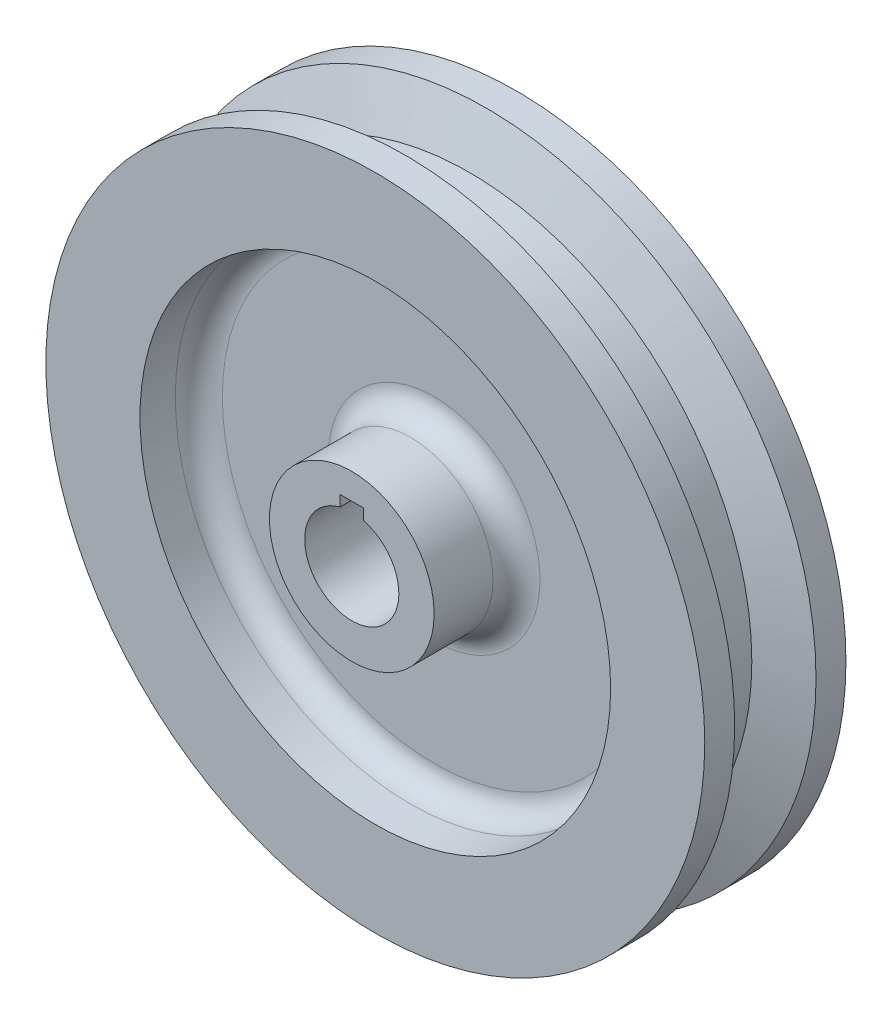
SolidWorks part; units mm, degrees
material "Cast Carbon Steel"
ref_plane "Front Plane" through (0, 0, 0) normal (0, 0, 1) x (1, 0, 0)
ref_plane "Top Plane" through (0, 0, 0) normal (0, 1, 0) x (1, 0, 0)
ref_plane "Right Plane" through (0, 0, 0) normal (1, 0, 0) x (0, 0, -1)
sketch "Sketch1" plane through (0, 0, 0) normal (1, 0, 0) x (0, 0, -1)
  line L0 (-48.3797, 0) -> (2370.6054, 0) construction
  line L1 (-1, 0.5) -> (1, 0.5)
  line L2 (1, 0.5) -> (1, 0.875)
  line L3 (1, 0.875) -> (0.125, 0.875)
  line L4 (0.125, 0.875) -> (0.125, 2.5)
  line L5 (0.125, 2.5) -> (0.75, 2.5)
  line L6 (0.75, 2.5) -> (0.75, 3.5)
  line L7 (0.75, 3.5) -> (0.432, 3.5)
  line L8 (0.432, 3.5) -> (0.25, 3)
  line L9 (0.25, 3) -> (-0.25, 3)
  line L10 (-0.25, 3) -> (-0.432, 3.5)
  line L11 (-0.432, 3.5) -> (-0.75, 3.5)
  line L12 (-0.75, 3.5) -> (-0.75, 2.5)
  line L13 (-0.75, 2.5) -> (-0.125, 2.5)
  line L14 (-0.125, 2.5) -> (-0.125, 0.875)
  line L15 (-0.125, 0.875) -> (-1, 0.875)
  line L16 (-1, 0.875) -> (-1, 0.5)
  point P5 (0, 3)
  point P20 (0, 0.5)
  point P21 (1, 0.6875)
  point P22 (0.591, 3.5)
  dimension "D1" = 0.25
  dimension "D2" = 1
  dimension "D3" = 1.75
  dimension "D4" = 5
  dimension "D5" = 7
  dimension "D6" = 0.5
  dimension "D7" = 2
  dimension "D8" = 1.5
  dimension "D9" = 0.5
  dimension "D10" = 40
revolve "Revolve1" add sketch "Sketch1" angle 360 about L0
fillet "Fillet1" radius 0.25 4 edges at (0.875, 0, -0.125) (2.5, 0, -0.125) (0.875, 0, 0.125) (2.5, 0, 0.125)
sketch "Sketch2" plane through (0, 0, 1) normal (0, 0, 1) x (1, 0, 0)
  line L1 (-0.125, 0.6) -> (0.125, 0.6)
  line L2 (-0.125, 0.6) -> (-0.125, 0.35)
  line L3 (-0.125, 0.35) -> (0.125, 0.35)
  line L4 (0.125, 0.6) -> (0.125, 0.35)
  point P4 (0, 0.6)
  dimension "D1" = 0.25
  dimension "D2" = 0.6
  dimension "D3" = 0.25
extrude "Cut-Extrude1" cut sketch "Sketch2" against normal through all
